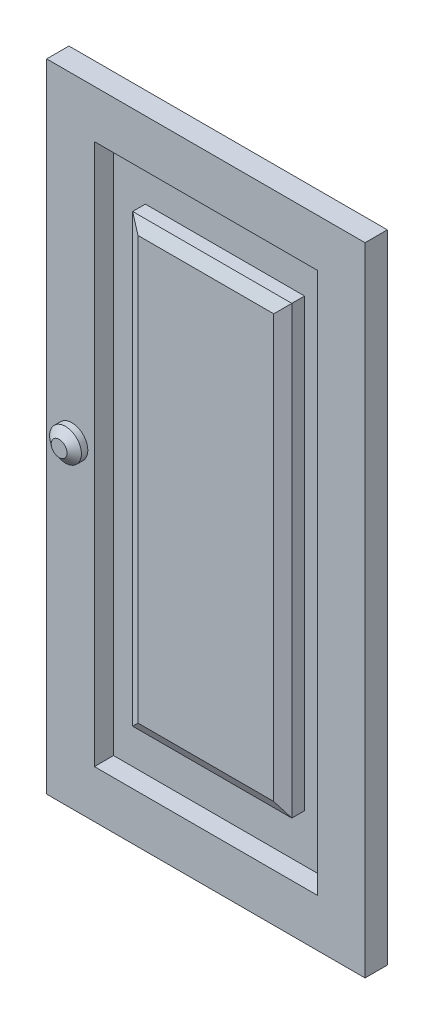
SolidWorks part; units mm, degrees
ref_plane "Alzado" through (0, 0, 0) normal (0, 0, 1) x (1, 0, 0)
ref_plane "Planta" through (0, 0, 0) normal (0, 1, 0) x (1, 0, 0)
ref_plane "Vista lateral" through (0, 0, 0) normal (1, 0, 0) x (0, 0, -1)
sketch "Croquis2" plane through (0, 0, 0) normal (0, 0, 1) x (1, 0, 0)
  line L1 (-5, -10) -> (5, -10)
  line L2 (-5, -10) -> (-5, 10)
  line L3 (-5, 10) -> (5, 10)
  line L4 (5, -10) -> (5, 10)
  line L5 (-5, -10) -> (5, 10) construction
  line L6 (-5, 10) -> (5, -10) construction
  point P0 (0, 0)
  dimension "D1" = 10
  dimension "D2" = 20
extrude "Saliente-Extruir1" add sketch "Croquis2" along normal blind 0.7
sketch "Croquis3" plane through (0, 0, 0.7) normal (0, 0, 1) x (1, 0, 0)
  line L1 (-3.5, -8.5) -> (3.5, -8.5)
  line L2 (-3.5, -8.5) -> (-3.5, 8.5)
  line L3 (-3.5, 8.5) -> (3.5, 8.5)
  line L4 (3.5, -8.5) -> (3.5, 8.5)
  line L5 (-3.5, -8.5) -> (3.5, 8.5) construction
  line L6 (-3.5, 8.5) -> (3.5, -8.5) construction
  point P0 (0, 0)
  dimension "D1" = 17
  dimension "D2" = 7
extrude "Cortar-Extruir1" cut sketch "Croquis3" against normal blind 0.6
sketch "Croquis4" plane through (0, 0, 0.1) normal (0, 0, 1) x (1, 0, 0)
  line L1 (-2.5, -7) -> (2.5, -7)
  line L2 (-2.5, -7) -> (-2.5, 7)
  line L3 (-2.5, 7) -> (2.5, 7)
  line L4 (2.5, -7) -> (2.5, 7)
  line L5 (-2.5, -7) -> (2.5, 7) construction
  line L6 (-2.5, 7) -> (2.5, -7) construction
  point P0 (0, 0)
  dimension "D1" = 14
  dimension "D2" = 5
extrude "Saliente-Extruir2" add sketch "Croquis4" along normal blind 0.6
chamfer "Chaflán1" distance 0.2 angle 61.5 4 edges at (0, -7, 0.7) (-2.5, 0, 0.7) (0, 7, 0.7) (2.5, 0, 0.7)
sketch "Croquis5" plane through (0, 0, 0.7) normal (0, 0, 1) x (1, 0, 0)
  circle A0 centre (-4.2081, 0) radius 0.5
extrude "Saliente-Extruir3" add sketch "Croquis5" along normal blind 0.4
chamfer "Chaflán2" distance 0.2 angle 51.5 1 edges at (-3.7081, 0, 1.1)
sketch "Croquis6" plane through (0, 0, 0.7) normal (0, 0, 1) x (1, 0, 0)
  line L0 (-2.052, 4.5) -> (1.9925, 4.5) construction
  line L1 (-2.5, 7) -> (2.5, 7) construction
  text T0 "BIENVENIDO" font "Century Gothic" height 0.5
  dimension "D1" = 2.5
